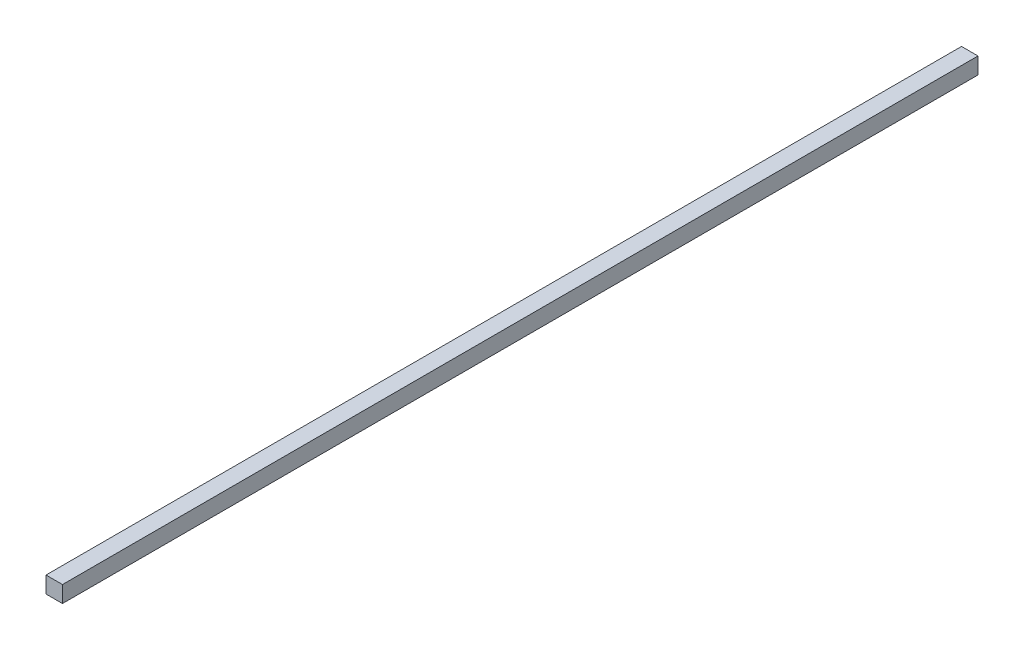
SolidWorks part; units mm, degrees
material "Pine"
ref_plane "Front Plane" through (0, 0, 0) normal (0, 0, 1) x (1, 0, 0)
ref_plane "Top Plane" through (0, 0, 0) normal (0, 1, 0) x (1, 0, 0)
ref_plane "Right Plane" through (0, 0, 0) normal (1, 0, 0) x (0, 0, -1)
sketch "Sketch1" plane through (0, 0, 0) normal (0, 0, 1) x (1, 0, 0)
  line L1 (-9, 9) -> (9, 9)
  line L2 (-9, 9) -> (-9, -9)
  line L3 (-9, -9) -> (9, -9)
  line L4 (9, 9) -> (9, -9)
  line L5 (-9, 9) -> (9, -9) construction
  line L6 (-9, -9) -> (9, 9) construction
  point P0 (0, 0)
  dimension "D1" = 18
  dimension "D2" = 18
extrude "Boss-Extrude1" add sketch "Sketch1" along normal blind 1000
